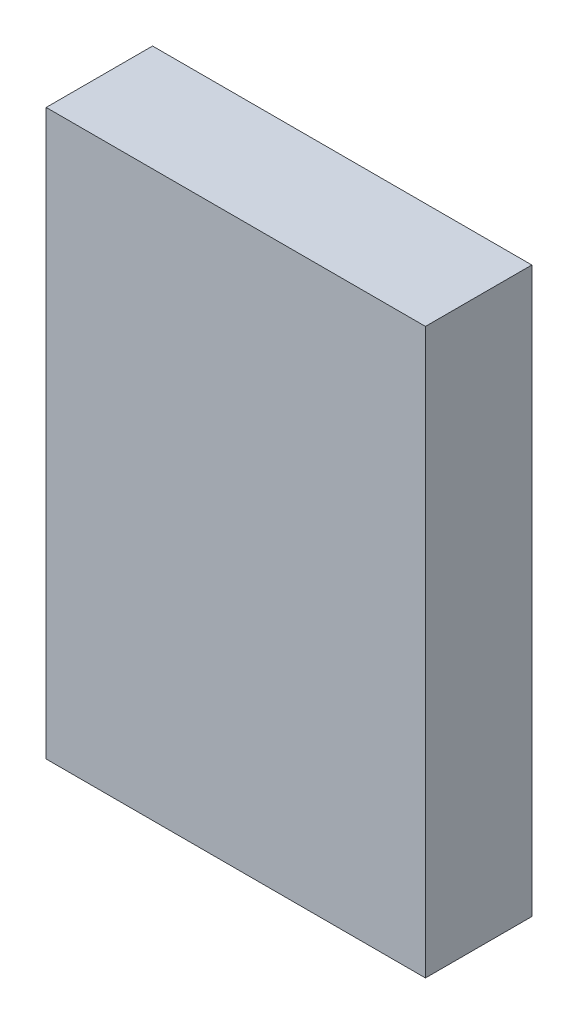
SolidWorks part; units mm, degrees
ref_plane "Front Plane" through (0, 0, 0) normal (0, 0, 1) x (1, 0, 0)
ref_plane "Top Plane" through (0, 0, 0) normal (0, 1, 0) x (1, 0, 0)
ref_plane "Right Plane" through (0, 0, 0) normal (1, 0, 0) x (0, 0, -1)
sketch "Sketch1" plane through (0, 0, 0) normal (0, 0, 1) x (1, 0, 0)
  line L1 (-41, 61) -> (41, 61)
  line L2 (-41, 61) -> (-41, -61)
  line L3 (-41, -61) -> (41, -61)
  line L4 (41, 61) -> (41, -61)
  point P4 (0, -61)
  point P7 (-41, 0)
  dimension "D1" = 82
  dimension "D2" = 122
extrude "Boss-Extrude1" add sketch "Sketch1" against normal blind 23
sketch "Sketch2" plane through (0, 0, -23) normal (0, 0, -1) x (-1, 0, 0)
  line L0 (-41, 61) -> (41, 61) construction
  line L1 (-38, 58) -> (38, 58)
  line L2 (-38, 58) -> (-38, -58)
  line L3 (-38, -58) -> (38, -58)
  line L4 (38, 58) -> (38, -58)
  line L5 (41, -61) -> (-41, -61) construction
  line L6 (-41, -61) -> (-41, 61) construction
  line L7 (41, 61) -> (41, -61) construction
  point P6 (0, -58)
  dimension "D1" = 3
  dimension "D2" = 3
  dimension "D3" = 3
  dimension "D4" = 3
extrude "Cut-Extrude1" cut sketch "Sketch2" against normal offset from surface (21 mm away) 2 up to face at (0, 0, 0)
sketch "Sketch6" plane through (0, 0, -23) normal (0, 0, -1) x (-1, 0, 0)
  line L0 (-38, 58) -> (-38, -58) construction
  line L1 (-39, 59) -> (39, 59)
  line L2 (-39, 59) -> (-39, -59)
  line L3 (-39, -59) -> (39, -59)
  line L4 (39, 59) -> (39, -59)
  line L5 (38, 58) -> (-38, 58) construction
  line L6 (38, -58) -> (38, 58) construction
  line L8 (-38, -58) -> (38, -58) construction
  dimension "D1" = 1
  dimension "D2" = 1
  dimension "D3" = 1
  dimension "D4" = 1
extrude "Cut-Extrude3" cut sketch "Sketch6" against normal blind 2
sketch "Sketch3" plane through (0, 0, -2) normal (0, 0, -1) x (-1, 0, 0)
  line L1 (38, 58) -> (-38, 58) construction
  line L2 (-38, 58) -> (-38, -58) construction
  circle A0 centre (30, 50) radius 4
  circle A1 centre (-30, 50) radius 4
  circle A2 centre (30, -20) radius 4
  circle A3 centre (-30, -20) radius 4
  dimension "D1" = 8
  dimension "D3" = 2
  dimension "D4" = 8
  dimension "D2" = 8
  dimension "D5" = 2
extrude "Boss-Extrude2" [suppressed] add sketch "Sketch3" along normal blind 3
sketch "Sketch4" [suppressed] plane through (0, 0, -5) normal (0, 0, -1) x (-1, 0, 0)
  circle A0 centre (-30, 50) radius 2
  circle A1 centre (30, 50.0168) radius 2
  circle A2 centre (30.0196, -19.9832) radius 2
  circle A3 centre (-29.9804, -20) radius 2
  dimension "D1" = 4
  dimension "D2" = 2
  dimension "D3" = 2
extrude "Boss-Extrude3" [suppressed] add sketch "Sketch4" along normal blind 17
sketch "Sketch5" [suppressed] plane through (0, 0, -22) normal (0, 0, -1) x (-1, 0, 0)
  circle A0 centre (-30, 50) radius 0.75
  circle A1 centre (30, 50.0168) radius 0.75
  circle A2 centre (30.0196, -19.9832) radius 0.75
  circle A3 centre (-29.9804, -20) radius 0.75
  dimension "D1" = 1.5
  dimension "D2" = 2
  dimension "D3" = 2
extrude "Cut-Extrude2" [suppressed] cut sketch "Sketch5" against normal blind 4.7
